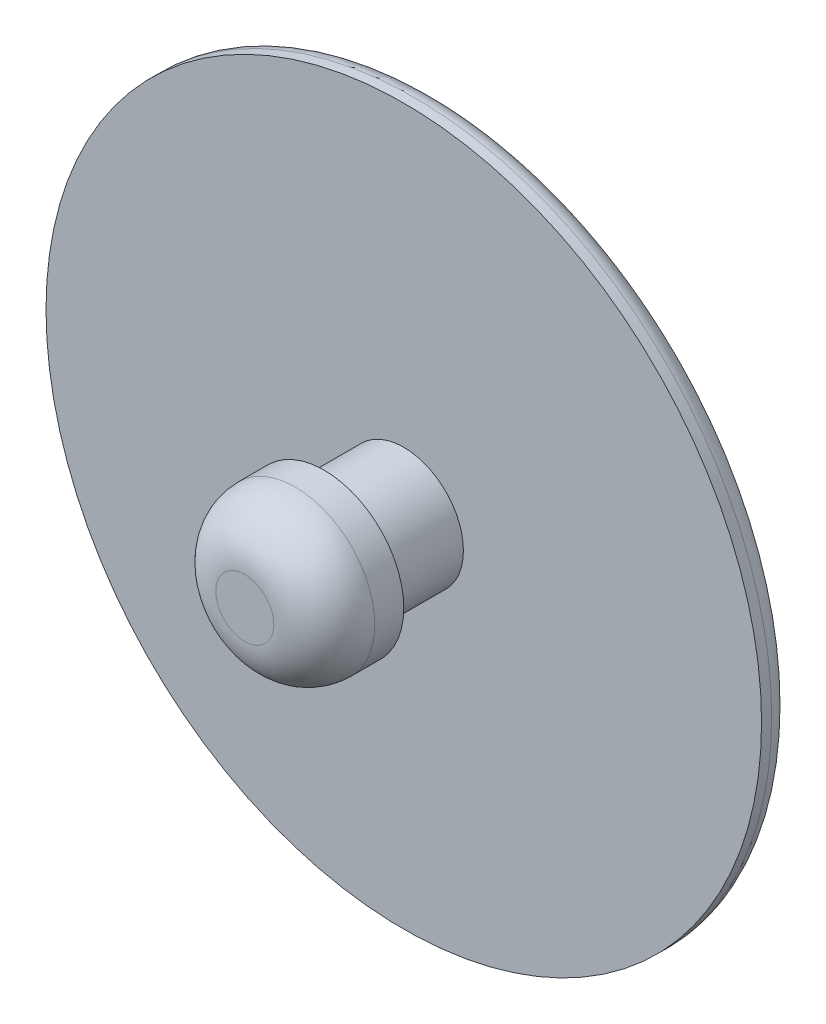
SolidWorks part; units mm, degrees
ref_plane "Front Plane" through (0, 0, 0) normal (0, 0, 1) x (1, 0, 0)
ref_plane "Top Plane" through (0, 0, 0) normal (0, 1, 0) x (1, 0, 0)
ref_plane "Right Plane" through (0, 0, 0) normal (1, 0, 0) x (0, 0, -1)
sketch "Sketch1" plane through (0, 0, 0) normal (0, 0, 1) x (1, 0, 0)
  circle A0 centre (0, 0) radius 9
  dimension "D1" = 18
extrude "Boss-Extrude1" add sketch "Sketch1" along normal blind 0.762
fillet "Fillet1" radius 0.508 1 edges at (9, 0, 0)
sketch "Sketch2" plane through (0, 0, 0.762) normal (0, 0, 1) x (1, 0, 0)
  circle A0 centre (0, 0) radius 1.5
  dimension "D1" = 3
extrude "Boss-Extrude2" add sketch "Sketch2" along normal blind 2
sketch "Sketch3" plane through (0, 0, 2.762) normal (0, 0, 1) x (1, 0, 0)
  circle A0 centre (0, 0) radius 2
  dimension "D1" = 4
extrude "Boss-Extrude3" add sketch "Sketch3" along normal blind 2
fillet "Fillet2" radius 1.27 1 edges at (2, 0, 4.762)
